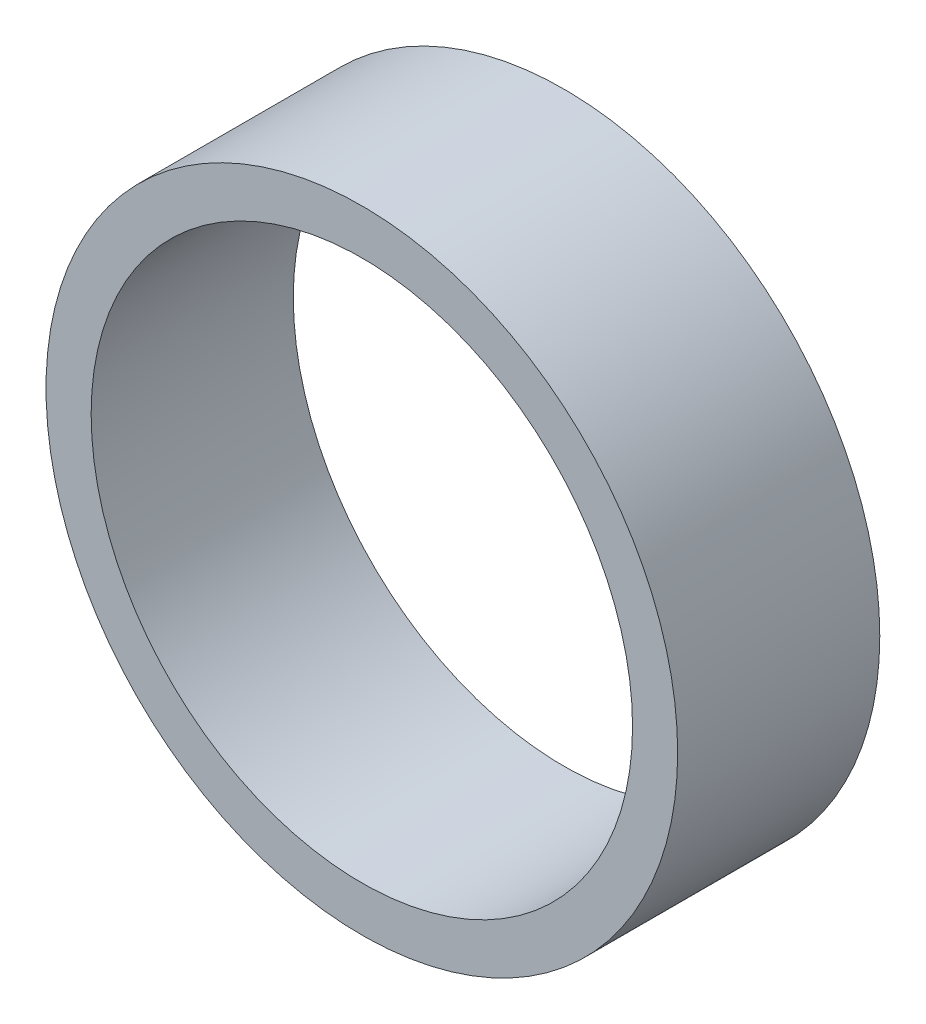
SolidWorks part; units mm, degrees
material "Rubber"
ref_plane "Front Plane" through (0, 0, 0) normal (0, 0, 1) x (1, 0, 0)
ref_plane "Top Plane" through (0, 0, 0) normal (0, 1, 0) x (1, 0, 0)
ref_plane "Right Plane" through (0, 0, 0) normal (1, 0, 0) x (0, 0, -1)
sketch "Sketch1" plane through (0, 0, 0) normal (0, 0, 1) x (1, 0, 0)
  circle A0 centre (0, 0) radius 9.525
  circle A1 centre (0, 0) radius 11.1125
  dimension "D1" = 19.05
  dimension "D2" = 1.5875
extrude "Boss-Extrude1" add sketch "Sketch1" along normal blind 7.112
